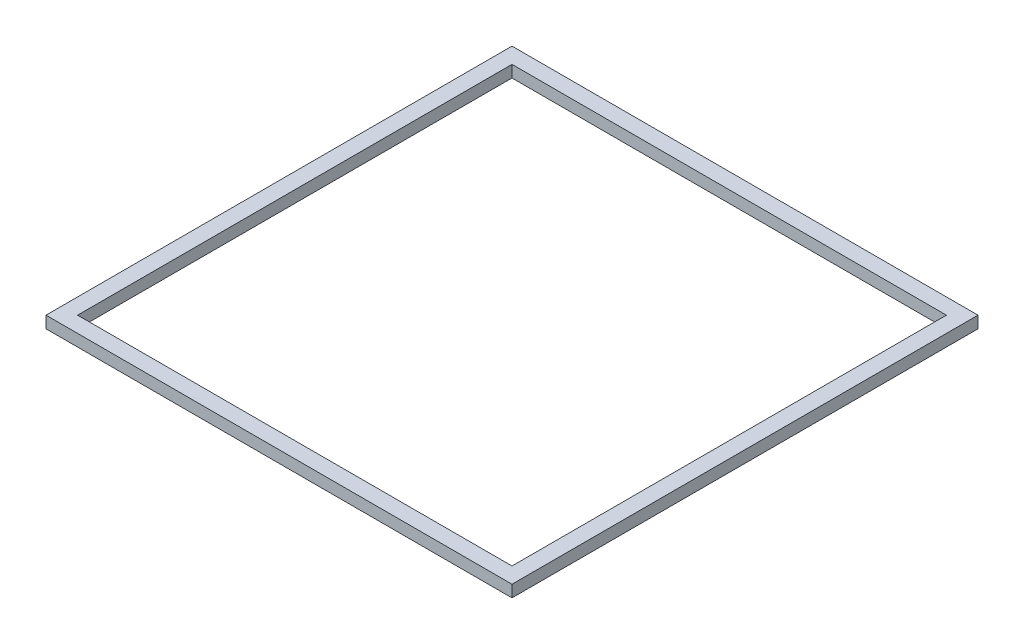
SolidWorks part; units mm, degrees
material "Concreto"
ref_plane "Plano frontal" through (0, 0, 0) normal (0, 0, 1) x (1, 0, 0)
ref_plane "Plano superior" through (0, 0, 0) normal (0, 1, 0) x (1, 0, 0)
ref_plane "Plano direito" through (0, 0, 0) normal (1, 0, 0) x (0, 0, -1)
sketch "Esboço1" plane through (0, 0, 0) normal (0, 1, 0) x (1, 0, 0)
  line L5 (-2750, 2750) -> (2750, 2750)
  line L6 (-2750, 2750) -> (-2750, -2750)
  line L11 (-2750, -2750) -> (2750, -2750)
  line L12 (2750, 2750) -> (2750, -2750)
  line L13 (-2750, 2750) -> (2750, -2750) construction
  line L14 (-2750, -2750) -> (2750, 2750) construction
  line L15 (-2950, 2950) -> (2950, 2950)
  line L16 (-2950, 2950) -> (-2950, -2950)
  line L17 (-2950, -2950) -> (2950, -2950)
  line L18 (2950, 2950) -> (2950, -2950)
  line L19 (-2950, 2950) -> (2950, -2950) construction
  line L20 (-2950, -2950) -> (2950, 2950) construction
  point P0 (0, 0)
  point P6 (0, 0)
  dimension "D1" = 5500
  dimension "D2" = 5500
  dimension "D3" = 200
  dimension "D4" = 200
extrude "Ressalto-extrusão1" add sketch "Esboço1" along normal blind 150
